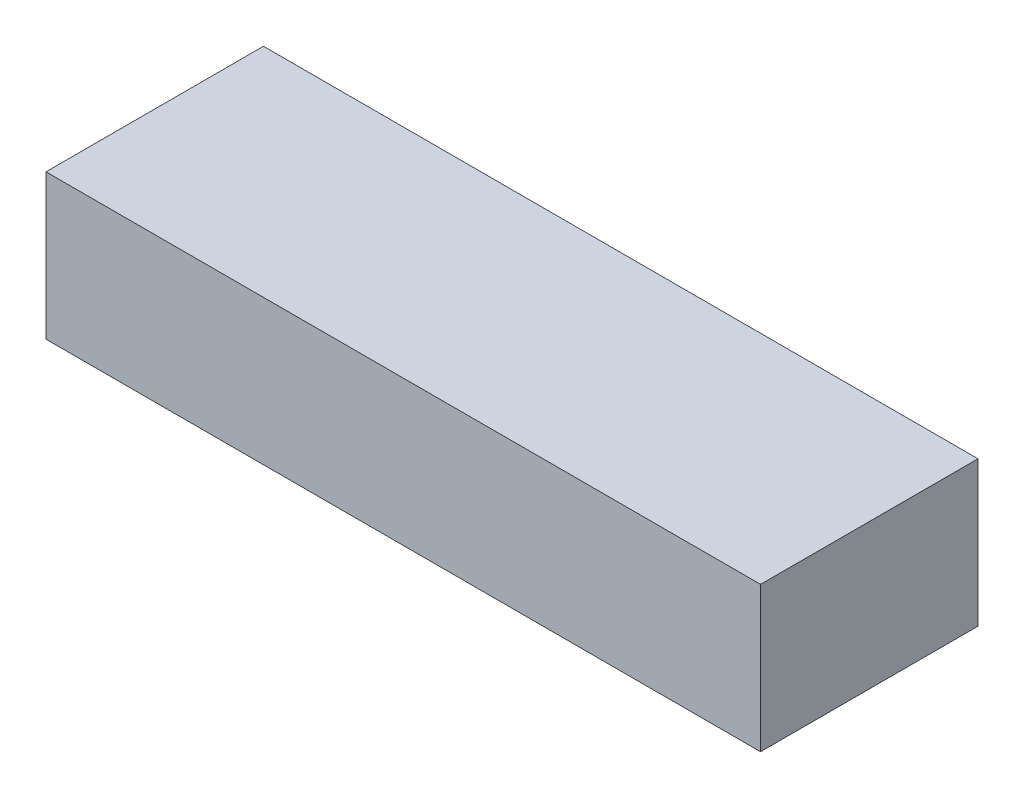
SolidWorks part; units mm, degrees
ref_plane "Front Plane" through (0, 0, 0) normal (0, 0, 1) x (1, 0, 0)
ref_plane "Top Plane" through (0, 0, 0) normal (0, 1, 0) x (1, 0, 0)
ref_plane "Right Plane" through (0, 0, 0) normal (1, 0, 0) x (0, 0, -1)
sketch "Sketch1" plane through (0, 0, 0) normal (0, 1, 0) x (1, 0, 0)
  line L1 (-69, -21) -> (69, -21)
  line L2 (-69, -21) -> (-69, 21)
  line L3 (-69, 21) -> (69, 21)
  line L4 (69, -21) -> (69, 21)
  line L5 (-69, -21) -> (69, 21) construction
  line L6 (-69, 21) -> (69, -21) construction
  point P0 (0, 0)
extrude "Boss-Extrude1" add sketch "Sketch1" along normal blind 28
sketch "Sketch3" plane through (69, 0, 0) normal (1, 0, 0) x (0, 0, -1)
  line L0 (0, 0) -> (0, -5) construction
  line L1 (-21, 0) -> (21, 0) construction
  line L2 (-15, -5) -> (15, -5)
  line L3 (-15, -5) -> (-10, 0)
  line L4 (15, -5) -> (10, 0)
  line L5 (10, 0) -> (-10, 0)
  point P7 (0, -5)
extrude "Boss-Extrude2" add sketch "Sketch3" against normal blind 105 from offset 14
